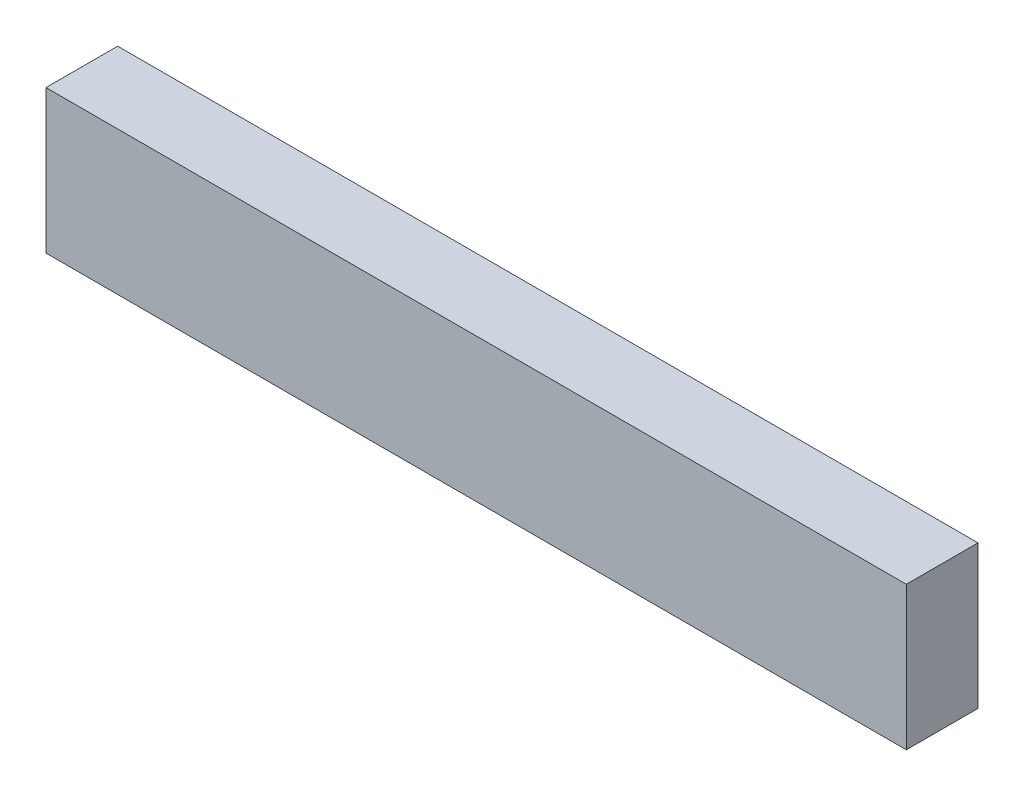
SolidWorks part; units mm, degrees
material "Pino"
ref_plane "Alzado" through (0, 0, 0) normal (0, 0, 1) x (1, 0, 0)
ref_plane "Planta" through (0, 0, 0) normal (0, 1, 0) x (1, 0, 0)
ref_plane "Vista lateral" through (0, 0, 0) normal (1, 0, 0) x (0, 0, -1)
sketch "Croquis1" plane through (0, 0, 0) normal (0, 1, 0) x (1, 0, 0)
  line L1 (-152.4, -12.7) -> (152.4, -12.7)
  line L2 (-152.4, -12.7) -> (-152.4, 12.7)
  line L3 (-152.4, 12.7) -> (152.4, 12.7)
  line L4 (152.4, -12.7) -> (152.4, 12.7)
  line L5 (-152.4, -12.7) -> (152.4, 12.7) construction
  line L6 (-152.4, 12.7) -> (152.4, -12.7) construction
  point P0 (0, 0)
  dimension "D1" = 25.4
  dimension "D2" = 304.8
extrude "Saliente-Extruir1" add sketch "Croquis1" along normal blind 50.8
